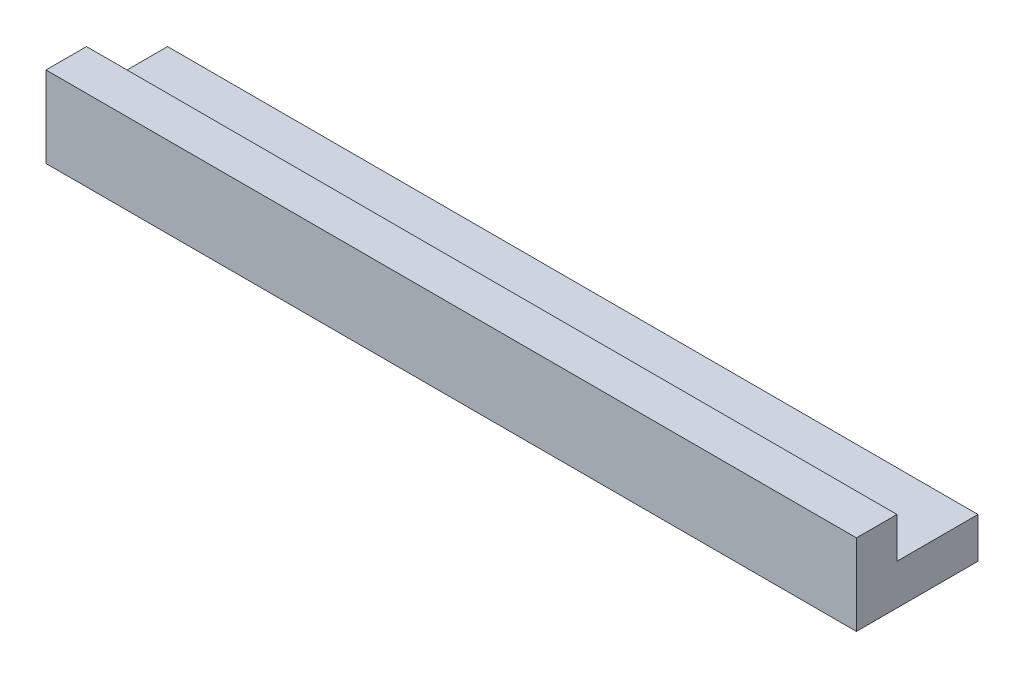
SolidWorks part; units mm, degrees
ref_plane "Front Plane" through (0, 0, 0) normal (0, 0, 1) x (1, 0, 0)
ref_plane "Top Plane" through (0, 0, 0) normal (0, 1, 0) x (1, 0, 0)
ref_plane "Right Plane" through (0, 0, 0) normal (1, 0, 0) x (0, 0, -1)
sketch "Sketch2" plane through (0, 0, 0) normal (1, 0, 0) x (0, 0, -1)
  line L0 (0, 0) -> (0, -2)
  line L5 (0, -2) -> (4, -2)
  line L6 (-2, 0) -> (-2, -4)
  line L7 (-2, -4) -> (4, -4)
  line L8 (4, -2) -> (4, -4)
  line L9 (0, 0) -> (-2, 0)
  dimension "D1" = 4
  dimension "D2" = 2
  dimension "D3" = 2
extrude "Boss-Extrude1" add sketch "Sketch2" along normal blind 40
